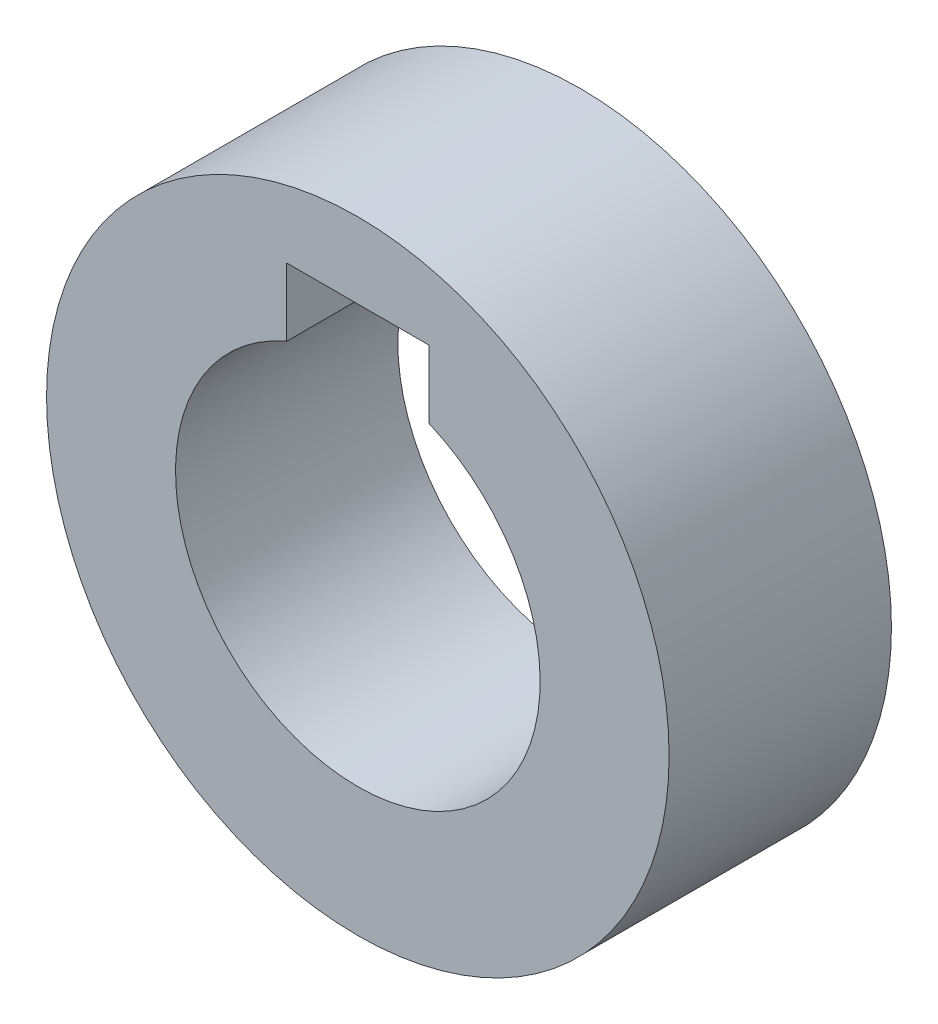
SolidWorks part; units mm, degrees
ref_plane "Front Plane" through (0, 0, 0) normal (0, 0, 1) x (1, 0, 0)
ref_plane "Top Plane" through (0, 0, 0) normal (0, 1, 0) x (1, 0, 0)
ref_plane "Right Plane" through (0, 0, 0) normal (1, 0, 0) x (0, 0, -1)
sketch "Sketch1" plane through (0, 0, 0) normal (0, 0, 1) x (1, 0, 0)
  line L0 (-1.6, 3.7749) -> (-1.6, 5.3)
  line L1 (-1.6, 5.3) -> (1.6, 5.3)
  line L2 (1.6, 5.3) -> (1.6, 3.7749)
  line L3 (0, 0) -> (0, 7) construction
  circle A0 centre (0, 0) radius 4.1 construction
  circle A1 centre (0, 0) radius 7
  arc A2 (-1.6, 3.7749) -> (1.6, 3.7749) centre (0, 0) ccw
  dimension "D1" = 8.2
  dimension "D2" = 14
  dimension "D3" = 3.2
  dimension "D4" = 5.3
extrude "Boss-Extrude1" add sketch "Sketch1" along normal blind 5
